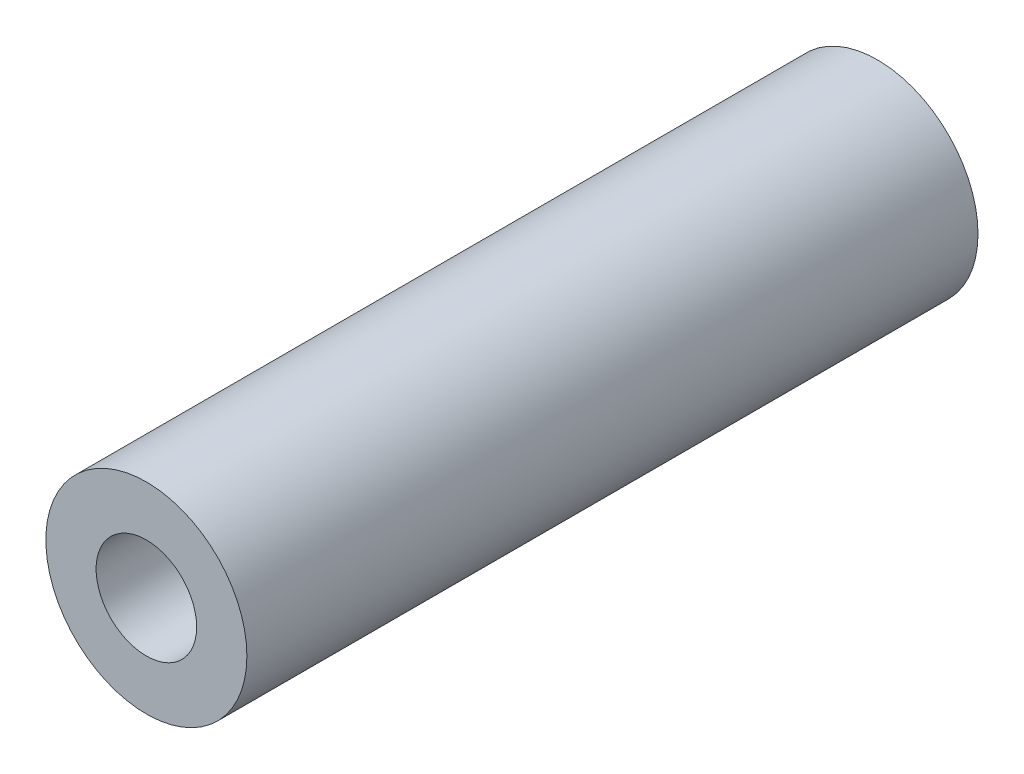
SolidWorks part; units mm, degrees
ref_plane "Front Plane" through (0, 0, 0) normal (0, 0, 1) x (1, 0, 0)
ref_plane "Top Plane" through (0, 0, 0) normal (0, 1, 0) x (1, 0, 0)
ref_plane "Right Plane" through (0, 0, 0) normal (1, 0, 0) x (0, 0, -1)
sketch "Sketch1" plane through (0, 0, 0) normal (0, 0, 1) x (1, 0, 0)
  circle A0 centre (0, 0) radius 11
  circle A1 centre (0, 0) radius 5.5
  dimension "D1" = 22
  dimension "D2" = 11
extrude "Boss-Extrude1" add sketch "Sketch1" along normal blind 80
